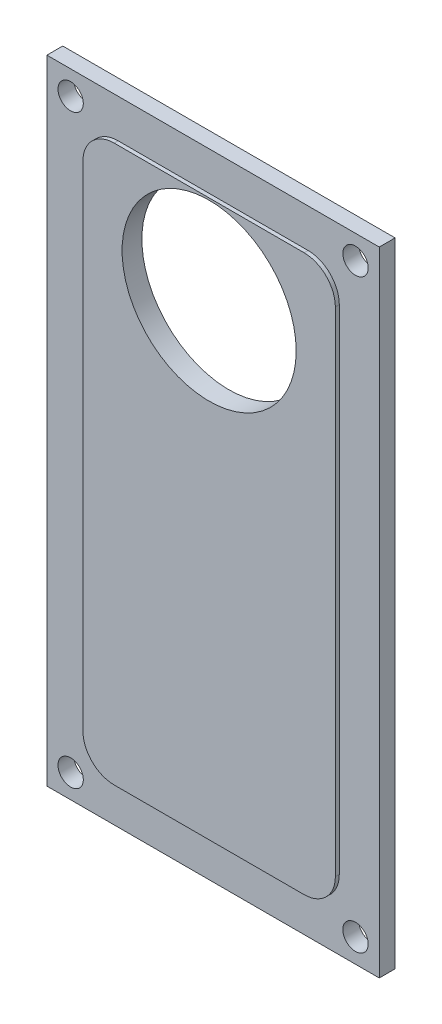
SolidWorks part; units mm, degrees
ref_plane "Front Plane" through (0, 0, 0) normal (0, 0, 1) x (1, 0, 0)
ref_plane "Top Plane" through (0, 0, 0) normal (0, 1, 0) x (1, 0, 0)
ref_plane "Right Plane" through (0, 0, 0) normal (1, 0, 0) x (0, 0, -1)
sketch "Sketch2" plane through (0, 0, 0) normal (0, 0, 1) x (1, 0, 0)
  line L1 (-21, 40) -> (21, 40)
  line L2 (-21, 40) -> (-21, -40)
  line L3 (-21, -40) -> (21, -40)
  line L4 (21, 40) -> (21, -40)
  line L5 (-21, 40) -> (21, -40) construction
  line L6 (-21, -40) -> (21, 40) construction
  point P0 (0, 0)
  dimension "D1" = 42
  dimension "D2" = 80
extrude "Boss-Extrude1" add sketch "Sketch2" along normal blind 2
ref_plane "Plane1" through (0, 0, 2) normal (0, 0, 1) x (1, 0, 0)
sketch "Sketch5" plane through (0, 0, 2) normal (0, 0, 1) x (1, 0, 0)
  line L1 (-15.95, 35.125) -> (15.95, 35.125)
  line L2 (-15.95, 35.125) -> (-15.95, -35.125)
  line L3 (-15.95, -35.125) -> (15.95, -35.125)
  line L4 (15.95, 35.125) -> (15.95, -35.125)
  line L5 (-15.95, 35.125) -> (15.95, -35.125) construction
  line L6 (-15.95, -35.125) -> (15.95, 35.125) construction
  point P0 (0, 0)
  dimension "D1" = 31.9
  dimension "D2" = 70.25
extrude "Boss-Extrude2" add sketch "Sketch5" along normal blind 0.5
fillet "Fillet1" radius 3.95 4 edges at (15.95, -35.125, 2.25) (-15.95, -35.125, 2.25) (15.95, 35.125, 2.25) (-15.95, 35.125, 2.25)
ref_plane "Plane2" through (0, 0, 2.5) normal (0, 0, 1) x (1, 0, 0)
sketch "Sketch7" plane through (0, 0, 2.5) normal (0, 0, 1) x (1, 0, 0)
  line L0 (12, 35.125) -> (-12, 35.125) construction
  circle A0 centre (0, 23.875) radius 11
  dimension "D2" = 22
  dimension "D1" = 11.25
extrude "Cut-Extrude1" cut sketch "Sketch7" against normal through all
ref_plane "Plane3" through (0, 0, 0) normal (0, 0, -1) x (-1, 0, 0)
sketch "Sketch8" plane through (0, 0, 0) normal (0, 0, -1) x (-1, 0, 0)
  line L0 (-21, 40) -> (21, 40) construction
  line L1 (21, 40) -> (21, -40) construction
  line L2 (-21, -40) -> (-21, 40) construction
  line L3 (21, -40) -> (-21, -40) construction
  circle A0 centre (18, 37) radius 1.6
  circle A1 centre (-18, 37) radius 1.6
  circle A2 centre (-18, -37) radius 1.6
  circle A3 centre (18, -37) radius 1.6
  dimension "D2" = 3.2
  dimension "D3" = 3
  dimension "D4" = 3.2
  dimension "D5" = 3
  dimension "D7" = 3
  dimension "D8" = 3.2
  dimension "D9" = 3
  dimension "D10" = 3
  dimension "D11" = 3
  dimension "D12" = 3.2
  dimension "D1" = 3
  dimension "D6" = 3
extrude "Cut-Extrude2" cut sketch "Sketch8" against normal through all
